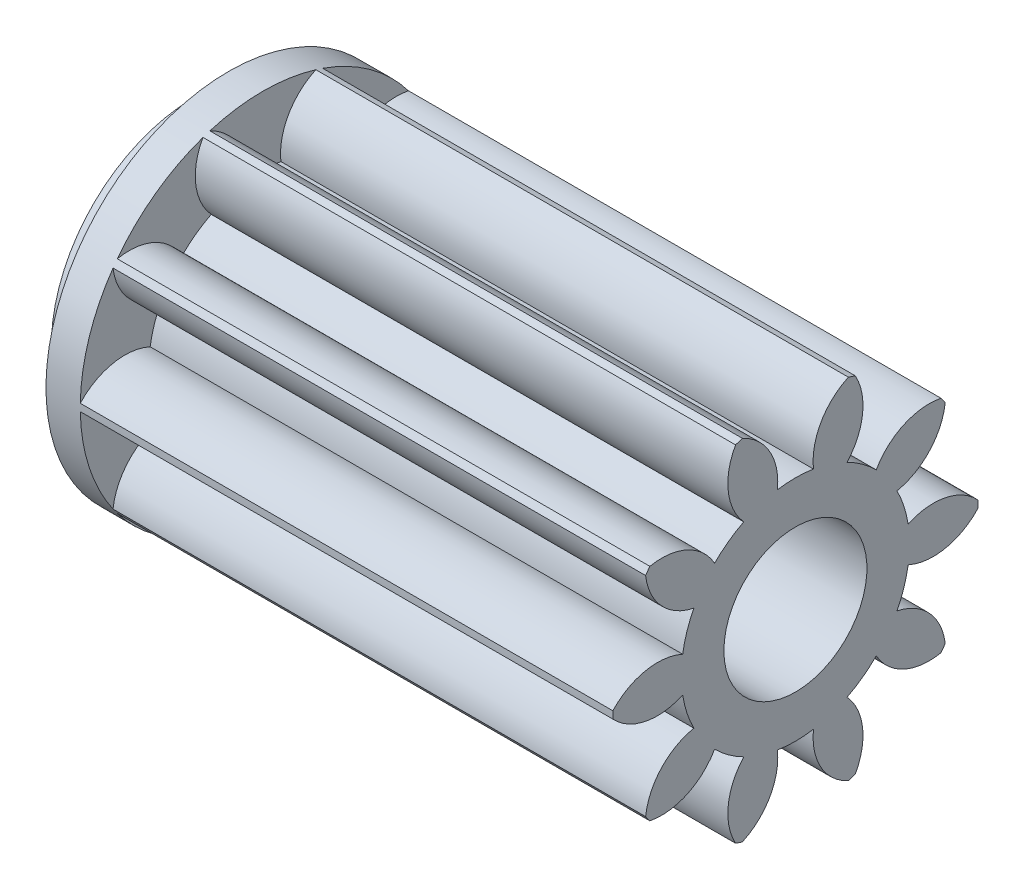
SolidWorks part; units mm, degrees
ref_plane "Plane1" through (0, 0, 0) normal (0, 0, 1) x (1, 0, 0)
ref_plane "Plane2" through (0, 0, 0) normal (0, 1, 0) x (1, 0, 0)
ref_plane "Plane3" through (0, 0, 0) normal (1, 0, 0) x (0, 0, -1)
sketch "HoldingSke" plane through (0, 0, 0) normal (0, 1, 0) x (1, 0, 0)
  line L0 (0, 0) -> (0.9848, -0.1736)
  line L1 (-15, 0) -> (100, 0) construction
  line L2 (0, 0) -> (-2.1039, 2.3779)
  line L3 (0, 0) -> (-11.863, 4.5341)
  line L4 (0, 0) -> (8.5048, 1.4996)
  line L5 (0, 0) -> (-46.8476, -17.4728)
  line L6 (0, 0) -> (-16.5793, -11.1861)
  line L7 (-2.1039, 2.3779) -> (8.6586, 51.2059)
  line L8 (-76.2, 54.61) -> (-75.3, 54.61)
  line L9 (-71.009, 38.7566) -> (-53.1078, 45.2721)
  line L10 (-76.2, 71.12) -> (104.1128, 71.12)
  line L11 (0, 0) -> (-20, 0)
  line L12 (-76.2, 101.6) -> (-76.162, 101.6)
  line L13 (24.9733, 27.94) -> (52.9518, 28.4284)
  line L14 (24.9733, 27.94) -> (24.9743, 27.94)
  line L15 (24.9733, 27.94) -> (100.4006, 29.5858)
  line L16 (-63.627, -1) -> (-12.827, -1)
  circle A0 centre (0, 0) radius 2.5
  circle A1 centre (0, 0) radius 3.749
  circle A2 centre (0, 0) radius 37.5
  circle A3 centre (0, 0) radius 2.5
  dimension "MHD" = 7.498
  dimension "Hub_dia" = 75
  dimension "Bore" = 5
  dimension "MBD" = 5
  dimension "Num_teeth" = 10
  dimension "Pitch" = 1
  dimension "Overall_len" = 50
  dimension "Show_teeth" = 10
  dimension "Thickness" = 20
  dimension "OAL" = 50.0001
  dimension "T_dim" = 0.9
  dimension "Ap" = 20
  dimension "H" = 19.05
  dimension "Pitch_radius" = 180.3128
  dimension "Width" = 20
  dimension "Backlash" = 0.038
  dimension "Addendum_fac" = 1
  dimension "Dedendum_fac" = 1.25
  dimension "Clearance_fac" = 0.25
  dimension "Dedendum_add" = 0.001
  dimension "Module" = 1
sketch "BasProSke" plane through (0, 0, 0) normal (0, 1, 0) x (1, 0, 0)
  line L0 (-10, 0) -> (60, 0) construction
  line L1 (0, 0) -> (0, 6)
  line L2 (0, 0) -> (17.5, 0)
  line L3 (17.5, 0) -> (17.5, 6)
  line L4 (17.5, 6) -> (0, 6)
  dimension "Thickness" = 17.5
  dimension "Diameter" = 12
revolve "Base-Revolve" add sketch "BasProSke" angle 360 about L0
sketch "TooCutSke" plane through (0, 0, 0) normal (1, 0, 0) x (0, 0, -1)
  line L1 (0, 0) -> (0, 107) construction
  line L2 (0, 0) -> (-0.8485, 4.9275) construction
  line L3 (0, 0) -> (-3.0584, 9.4126) construction
  line L4 (-0.8485, 4.9275) -> (-1.5292, 4.7063) construction
  arc A0 (0.5928, 3.7018) -> (-0.5928, 3.7018) centre (0, 0) ccw
  arc A1 (1.7758, 5.7578) -> (-1.7758, 5.7578) centre (0, 0) ccw
  circle A2 centre (0, 0) radius 5 construction
  circle A3 centre (0, 0) radius 4.6985 construction
  arc A4 (-0.5928, 3.7018) -> (-1.7758, 5.7578) centre (-2.5801, 3.9267) ccw
  arc A5 (1.7758, 5.7578) -> (0.5928, 3.7018) centre (2.5801, 3.9267) ccw
  dimension "Root_dia" = 7.498
  dimension "Overcut_dia" = 12.0508
  dimension "Pitch_dia" = 10
  dimension "Base_dia" = 9.3969
  dimension "Flank_rad" = 2
  dimension "Half_ang" = 18
  dimension "Half_CT" = 0.7157
extrude "ToothCut" cut sketch "TooCutSke" along normal through all
fillet "Breaks" [suppressed] radius 0.02
fillet "RootFillets" [suppressed] radius 0.251
pattern_circular "TeethCuts" count 10 every 36 about axis through (-10, 0, 0) along (1, 0, 0) of "ToothCut", "RootFillets", "Breaks"
sketch "HubNeaOneSke" plane through (0, 0, 0) normal (-1, 0, 0) x (0, 0, 1)
  circle A0 centre (0, 0) radius 3.749
  dimension "Diameter" = 7.498
extrude "HubNearOne" [suppressed] add sketch "HubNeaOneSke" along normal blind 32.5001
sketch "HubNeaBotSke" plane through (0, 0, 0) normal (-1, 0, 0) x (0, 0, 1)
  circle A0 centre (0, 0) radius 3.749
  dimension "Diameter" = 7.498
extrude "HubNearBoth" [suppressed] add sketch "HubNeaBotSke" along normal blind 16.25
ref_plane "FarPln" through (17.5, 0, 0) normal (1, 0, 0) x (0, 0, -1)
sketch "HubFarSke" plane through (17.5, 0, 0) normal (1, 0, 0) x (0, 0, -1)
  circle A0 centre (0, 0) radius 3.749
  dimension "Diameter" = 7.498
extrude "HubFar" [suppressed] add sketch "HubFarSke" along normal blind 16.25
sketch "BorSke" plane through (0, 0, 0) normal (1, 0, 0) x (0, 0, -1)
  circle A0 centre (0, 0) radius 2.35
  dimension "Diameter" = 4.7
extrude "Bore" cut sketch "BorSke" along normal mid plane 100.0001
sketch "KeySke" plane through (0, 0, 0) normal (1, 0, 0) x (0, 0, -1)
  line L0 (-1, 0) -> (-1, 3.4)
  line L1 (-1, 3.4) -> (1, 3.4)
  line L2 (1, 3.4) -> (1, 0)
  line L3 (0, 0) -> (0, 34) construction
  line L4 (-1, 0) -> (1, 0)
  dimension "Offset" = 3.4
extrude "Keyway" [suppressed] cut sketch "KeySke" along normal mid plane 100.0001
pattern_circular "Keyway2" [suppressed] count 2 every 90 about axis through (-10, 0, 0) along (1, 0, 0)
scale "Масштаб1" scale about centroid uniform scaling yes scale factor 1.065
sketch "Эскиз2" plane through (0, 0, 0) normal (0, 1, 0) x (1, 0, 0)
  line L0 (0, 0) -> (-5.94, 0) construction
  line L1 (-0.5688, 5.0942) -> (-0.5688, 2.8281) construction
  line L2 (-0.5688, 3.5) -> (-0.5688, 6.39)
  line L3 (-0.5688, 6.39) -> (-1.7688, 6.39)
  line L4 (-1.7688, 6.39) -> (-1.7687, 5)
  line L5 (-1.7687, 5) -> (-2.9688, 5)
  line L6 (-2.9688, 5) -> (-2.9687, 3.9243)
  line L7 (-2.9687, 3.9243) -> (-2.5445, 3.5)
  line L8 (-2.5445, 3.5) -> (-0.5688, 3.5)
  dimension "D1" = 7
  dimension "D2" = 12.78
  dimension "D3" = 1.2
  dimension "D4" = 1.2
  dimension "D5" = 10
  dimension "D6" = 45
  dimension "D7" = 0.6
revolve "Повернуть1" add sketch "Эскиз2" angle 360 about L0
equation "' \"Module@HoldingSke\" = 6.35"
equation "' \"Num_teeth@HoldingSke\" = 12"
equation "' \"Ap@HoldingSke\" =  20"
equation "' \"Ap@HoldingSke\" = 20"
equation "' \"Width@HoldingSke\" = 0.5 * 25.4"
equation "' \"Hub_dia@HoldingSke\"= 1 * 25.4"
equation "' \"Hub_dia@HoldingSke\" = 1 * 25.4"
equation "' \"Overall_len@HoldingSke\" = 1.0 * 25.4"
equation "' \"Bore@HoldingSke\" = 0.75 * 25.4"
equation "' \"T_dim@HoldingSke\" = 0.1 * 25.4"
equation "' \"Width@KeySke\" = 0.25 * 25.4"
equation "' \"Show_teeth@HoldingSke\" = 13"
equation "' \"Backlash@HoldingSke\" = 0.009 * 25.4"
equation "' \"Addendum_fac@HoldingSke\" = 1.0"
equation "' \"Dedendum_fac@HoldingSke\" = 1.25"
equation "' \"Dedendum_add@HoldingSke\" = 0.00005 * 25.4"
equation "' \"Clearance_fac@HoldingSke\" = 0.25"
equation "\"Pitch@HoldingSke\" = 1 / \"Module@HoldingSke\""
equation "\"Overcut_dia@TooCutSke\" = (\"Num_teeth@HoldingSke\" + 2 * \"Addendum_fac@HoldingSke\") / \"Pitch@HoldingSke\" + 0.002 * 25.4"
equation "\"Pitch_dia@TooCutSke\" = \"Num_teeth@HoldingSke\" / \"Pitch@HoldingSke\""
equation "\"Base_dia@TooCutSke\" = \"Num_teeth@HoldingSke\" / \"Pitch@HoldingSke\" * cos((\"Ap@HoldingSke\"  * 3.14159265 / 180))"
equation "\"Root_dia@TooCutSke\" = (\"Num_teeth@HoldingSke\" + 2) / \"Pitch@HoldingSke\" - 2 * (\"Addendum_fac@HoldingSke\" + \"Dedendum_fac@HoldingSke\") / \"Pitch@HoldingSke\" - \"Dedendum_add@HoldingSke\" * 2"
equation "\"Half_ang@TooCutSke\" = 180 / \"Num_teeth@HoldingSke\""
equation "\"Half_CT@TooCutSke\" = \"Num_teeth@HoldingSke\" / \"Pitch@HoldingSke\" * sin((3.14159265 / 2 / \"Num_teeth@HoldingSke\")) / 2 - 7 * \"Backlash@HoldingSke\" / 4"
equation "\"Flank_rad@TooCutSke\" = \"Num_teeth@HoldingSke\" / \"Pitch@HoldingSke\" / 5"
equation "\"Radius@RootFillets\" = \"Clearance_fac@HoldingSke\" / \"Pitch@HoldingSke\" + \"Dedendum_add@HoldingSke\""
equation "\"Break_rad@Breaks\" = 0.02 / \"Pitch@HoldingSke\""
equation "\"Thickness@HoldingSke\" = \"Width@HoldingSke\""
equation "\"OAL@HoldingSke\" = \"Thickness@HoldingSke\""
equation "\"MHD@HoldingSke\" = (\"Num_teeth@HoldingSke\" + 2) / \"Pitch@HoldingSke\" - 2 * (\"Addendum_fac@HoldingSke\" + \"Dedendum_fac@HoldingSke\")  / \"Pitch@HoldingSke\" - \"Dedendum_add@HoldingSke\" * 2"
equation "\"MBD@HoldingSke\" = (\"Num_teeth@HoldingSke\" + 2) / \"Pitch@HoldingSke\" - 2 * (\"Addendum_fac@HoldingSke\" + \"Dedendum_fac@HoldingSke\")  / \"Pitch@HoldingSke\" - \"Dedendum_add@HoldingSke\" * 2 - 0.002 * 25.4"
equation "\"MHD@HoldingSke\" = ((sgn( \"MHD@HoldingSke\" - \"Hub_dia@HoldingSke\" )-1)*( \"MHD@HoldingSke\" - \"Hub_dia@HoldingSke\" ))/-2+ \"Hub_dia@HoldingSke\""
equation "\"MBD@HoldingSke\" = ((sgn( \"MBD@HoldingSke\" - \"Bore@HoldingSke\" )-1)*( \"MBD@HoldingSke\" - \"Bore@HoldingSke\" ))/-2+ \"Bore@HoldingSke\""
equation "\"OAL@HoldingSke\" = ((sgn( \"OAL@HoldingSke\" - \"Overall_len@HoldingSke\" )+1)*( \"OAL@HoldingSke\" - \"Overall_len@HoldingSke\" ))/2 + \"Overall_len@HoldingSke\" + 0.000002 * 25.4"
equation "\"Num_teeth@TeethCuts\" = int( \"Show_teeth@HoldingSke\" ) + 1"
equation "\"Num_teeth@TeethCuts\" = ((sgn( \"Num_teeth@TeethCuts\" - \"Num_teeth@HoldingSke\" )-1)*( \"Num_teeth@TeethCuts\" - \"Num_teeth@HoldingSke\" ))/-2+ \"Num_teeth@HoldingSke\""
equation "\"Num_teeth@TeethCuts\" = ((sgn( \"Num_teeth@TeethCuts\" - 2.0)+1)*( \"Num_teeth@TeethCuts\" - 2.0))/2 +2.0"
equation "\"Angle@TeethCuts\" = 360.0 / \"Num_teeth@HoldingSke\""
equation "\"Diameter@BasProSke\" = (\"Num_teeth@HoldingSke\" + 2 * \"Addendum_fac@HoldingSke\") / \"Pitch@HoldingSke\""
equation "' \"Fillet_rad@BasProSke\" =  \"Thickness@HoldingSke\" * 0.05"
equation "' \"Fillet_rad@BasProSke\" = \"Thickness@HoldingSke\" * 0.05"
equation "\"MHD@HoldingSke\" = ((sgn( \"MHD@HoldingSke\" - \"Root_dia@TooCutSke\" )-1)*( \"MHD@HoldingSke\" - \"Root_dia@TooCutSke\" ))/-2+ \"Root_dia@TooCutSke\""
equation "\"Diameter@HubNeaOneSke\" = \"MHD@HoldingSke\""
equation "\"Length@HubNearOne\" = \"OAL@HoldingSke\" - \"Thickness@BasProSke\""
equation "\"Diameter@HubNeaBotSke\" = \"MHD@HoldingSke\""
equation "\"Length@HubNearBoth\" = ( \"OAL@HoldingSke\" - \"Thickness@BasProSke\" ) / 2.0"
equation "\"Thickness@FarPln\" = \"Thickness@BasProSke\""
equation "\"Diameter@HubFarSke\" = \"MHD@HoldingSke\""
equation "\"Length@HubFar\" = ( \"OAL@HoldingSke\" - \"Thickness@BasProSke\" ) / 2.0"
equation "\"D1@Bore\" = \"OAL@HoldingSke\" * 2.0"
equation "\"D1@Keyway\" = \"OAL@HoldingSke\" * 2.0"
equation "\"Offset@KeySke\" = \"T_dim@HoldingSke\" + \"MBD@HoldingSke\" / 2.0"
